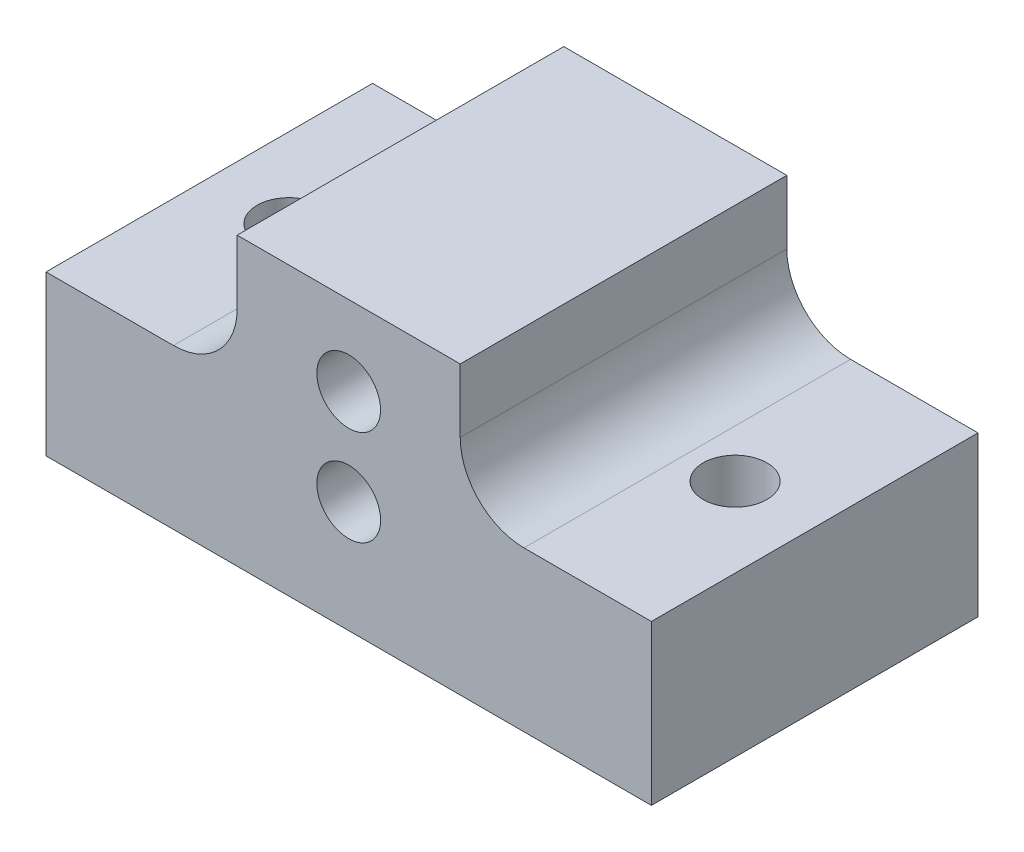
SolidWorks part; units mm, degrees
ref_plane "前视基准面" through (0, 0, 0) normal (0, 0, 1) x (1, 0, 0)
ref_plane "上视基准面" through (0, 0, 0) normal (0, 1, 0) x (1, 0, 0)
ref_plane "右视基准面" through (0, 0, 0) normal (1, 0, 0) x (0, 0, -1)
sketch "草图1" plane through (0, 0, 0) normal (1, 0, 0) x (0, 0, -1)
  line L1 (-7, 18) -> (7, 18)
  line L2 (-7, 18) -> (-7, 14)
  line L3 (-7, 0) -> (7, 0)
  line L4 (7, 18) -> (7, 14)
  line L5 (-19, 10) -> (-11, 10)
  line L6 (-19, 10) -> (-19, 0)
  line L7 (-19, 0) -> (-7, 0)
  line L9 (11, 10) -> (19, 10)
  line L11 (7, 0) -> (19, 0)
  line L12 (19, 10) -> (19, 0)
  arc A0 (11, 10) -> (7, 14) centre (11, 14) cw
  arc A1 (-7, 14) -> (-11, 10) centre (-11, 14) cw
  circle A2 centre (0, 13) radius 2
  circle A3 centre (0, 7) radius 2
  point P10 (0, 0)
  point P16 (0, 18)
  dimension "D7" = 4
  dimension "D9" = 7
  dimension "D1" = 14
  dimension "D2" = 18
  dimension "D3" = 10
  dimension "D4" = 10
  dimension "D5" = 12
  dimension "D6" = 12
  dimension "D8" = 14
  dimension "D10" = 6
extrude "凸台-拉伸1" add sketch "草图1" along normal blind 20.5
sketch "草图2" plane through (0, 10, 0) normal (0, 1, 0) x (1, 0, 0)
  circle A0 centre (10.25, 14) radius 2
  circle A1 centre (10.25, -14) radius 2
  dimension "D1" = 14
  dimension "D2" = 14
extrude "切除-拉伸1" cut sketch "草图2" against normal blind 20.5
move or copy body "实体-移动/复制1" bodies to move or copy 107 copy no rotation origin (10.25, 0, 0) rotation axis (0, -1, 0) rotation angle 90
